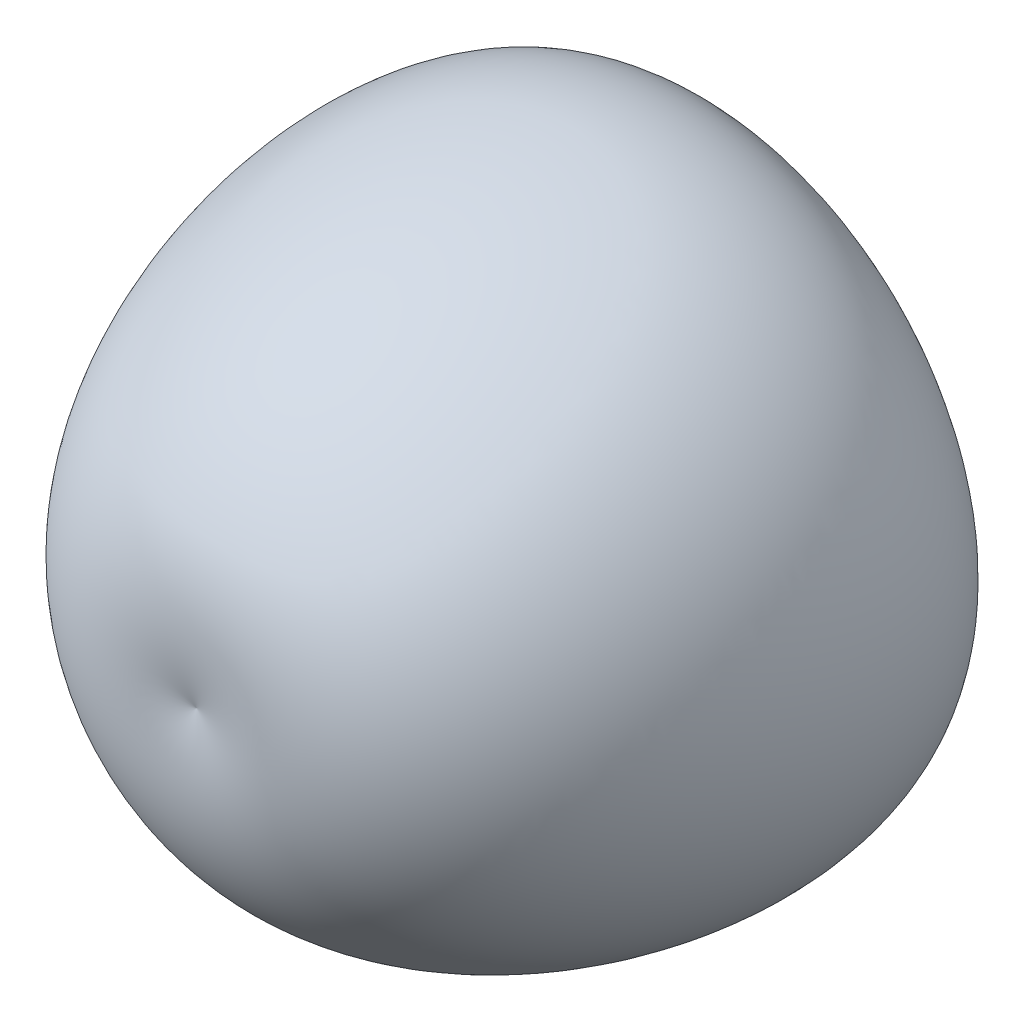
SolidWorks part; units mm, degrees
ref_plane "Front Plane" through (0, 0, 0) normal (0, 0, 1) x (1, 0, 0)
ref_plane "Top Plane" through (0, 0, 0) normal (0, 1, 0) x (1, 0, 0)
ref_plane "Right Plane" through (0, 0, 0) normal (1, 0, 0) x (0, 0, -1)
sketch "Sketch1" plane through (0, 0, 0) normal (0, 1, 0) x (1, 0, 0)
  line L0 (0, 15) -> (0, 0)
  spline S0 degree 3 poles (0, 15) (17.2075, 30.2182) (13.5335, -3.9214) (0, 0) knots 0 0 0 0 1 1 1 1
  point P4 (9.2819, 18)
  point P6 (7.547, 16.5253)
  point P7 (0, 0)
  point P8 (8.8482, 5.7687)
  point P9 (9.4554, 19.9952)
  point P10 (10.4096, 17.3928)
  point P11 (10.1494, 6.2024)
  dimension "D1" = 15
revolve "Revolve1" add sketch "Sketch1" angle 360 about L0
sketch "Sketch2" plane through (0, 0, 0) normal (0, 0, 1) x (1, 0, 0)
  circle A0 centre (0, 0) radius 0.5
  dimension "D1" = 1
extrude "Boss-Extrude4" add sketch "Sketch2" against normal blind 22
sketch "Sketch4" [suppressed] plane through (0, 0, 0) normal (0, 1, 0) x (1, 0, 0)
  line L0 (0, 5.0126) -> (0, 34.9747) construction
  spline S0 degree 2 poles (0, 20.8584) (2.4714, 21.6125) (5, 20.9494) knots 0 0 0 1 1 1
  point P2 (0, 20.8584)
  point P4 (0, 0)
  point P7 (0, 0)
  point P8 (0, 0)
  point P9 (0, 0)
  point P10 (0, 0)
  dimension "D1" = 5
sketch "Sketch12" plane through (0, 0, 0) normal (1, 0, 0) x (0, 0, -1)
